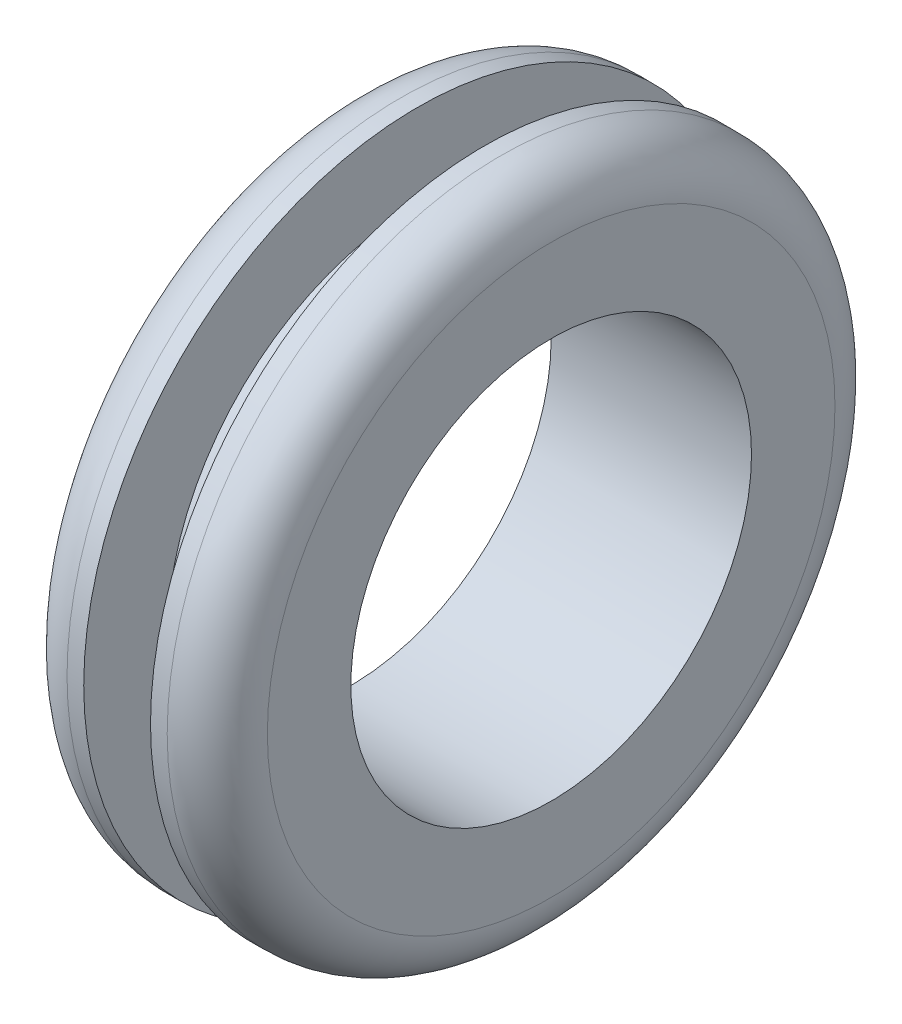
SolidWorks part; units mm, degrees
ref_plane "Спереди" through (0, 0, 0) normal (0, 0, 1) x (1, 0, 0)
ref_plane "Сверху" through (0, 0, 0) normal (0, 1, 0) x (1, 0, 0)
ref_plane "Справа" through (0, 0, 0) normal (1, 0, 0) x (0, 0, -1)
sketch "Эскиз1" plane through (0, 0, 0) normal (0, 0, 1) x (1, 0, 0)
  line L0 (-29.11, 0) -> (42.4811, 0) construction
  line L1 (-17.9674, 0) -> (-11.9674, 0)
  line L2 (-13.9674, 10) -> (-11.9674, 10)
  line L3 (-17.9674, 0) -> (-17.9674, 10)
  line L4 (-17.9674, 10) -> (-15.9674, 10)
  line L5 (-11.9674, 0) -> (-11.9674, 10)
  line L7 (-15.9674, 10) -> (-15.9674, 7.5)
  line L8 (-15.9674, 7.5) -> (-13.9674, 7.5)
  line L9 (-13.9674, 10) -> (-13.9674, 7.5)
  dimension "D1" = 6
  dimension "D2" = 2
  dimension "D3" = 2
  dimension "D5" = 7.5
  dimension "D6" = 10
revolve "Повернуть1" add sketch "Эскиз1" angle 360 about L0
sketch "Эскиз2" plane through (-11.9674, 0, 0) normal (1, 0, 0) x (0, 0, -1)
  circle A0 centre (0, 0) radius 6
  dimension "D1" = 12
extrude "Вырез-Вытянуть1" cut sketch "Эскиз2" against normal blind 6
fillet "Скругление1" radius 1.5
